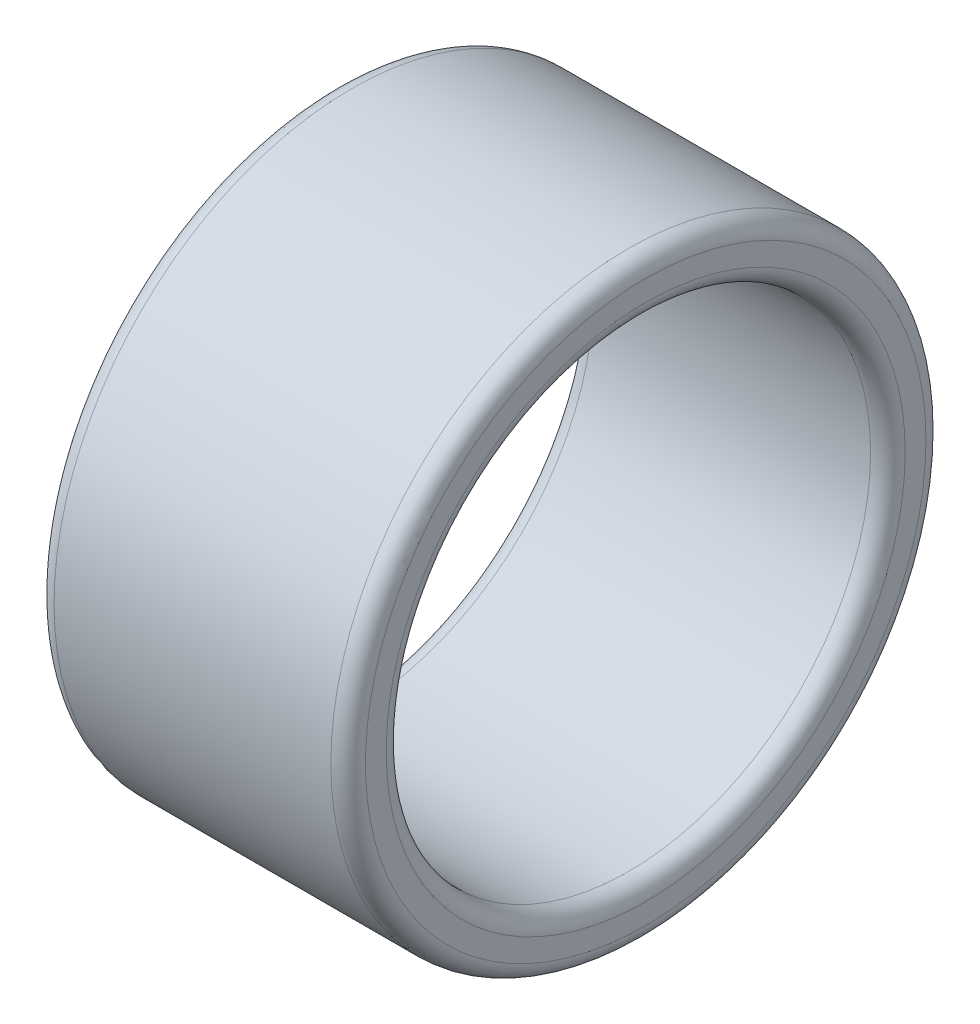
SolidWorks part; units mm, degrees
ref_plane "Front Plane" through (0, 0, 0) normal (0, 0, 1) x (1, 0, 0)
ref_plane "Top Plane" through (0, 0, 0) normal (0, 1, 0) x (1, 0, 0)
ref_plane "Right Plane" through (0, 0, 0) normal (1, 0, 0) x (0, 0, -1)
sketch "Sketch2" plane through (0, 0, 0) normal (1, 0, 0) x (0, 0, -1)
  circle A0 centre (0, 0) radius 34.4
  circle A1 centre (0, 0) radius 28
  dimension "D1" = 68.8
  dimension "D2" = 56
extrude "Boss-Extrude1" add sketch "Sketch2" along normal blind 36
fillet "Fillet1" radius 2 4 edges at (36, 0, -34.4) (0, 0, -34.4) (0, 0, -28) (36, 0, -28)
